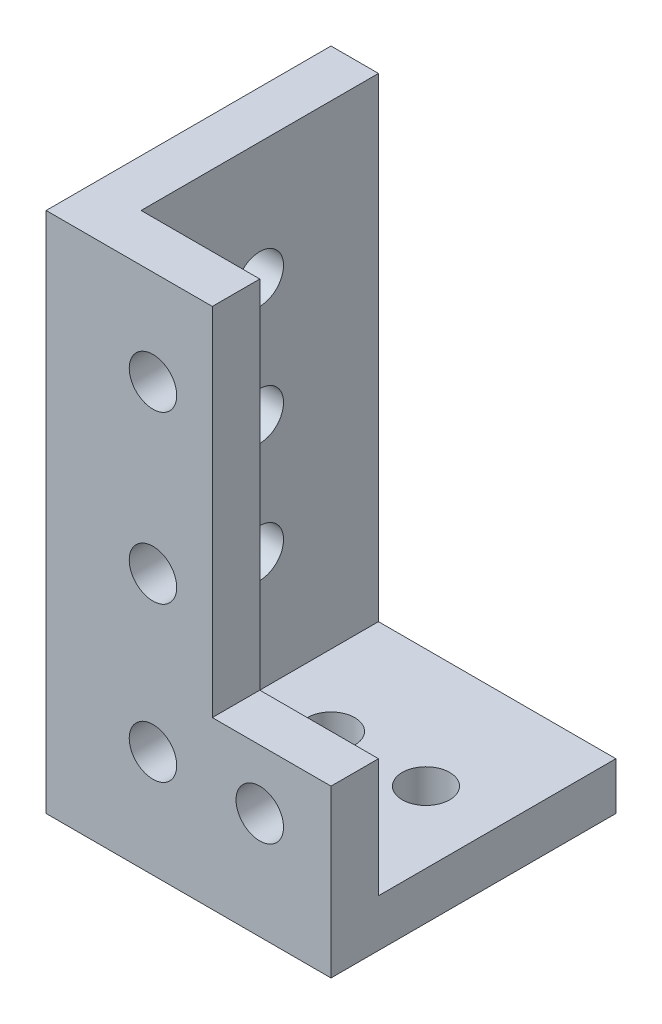
SolidWorks part; units mm, degrees
ref_plane "Front Plane" through (0, 0, 0) normal (0, 0, 1) x (1, 0, 0)
ref_plane "Top Plane" through (0, 0, 0) normal (0, 1, 0) x (1, 0, 0)
ref_plane "Right Plane" through (0, 0, 0) normal (1, 0, 0) x (0, 0, -1)
sketch "Sketch1" plane through (0, 0, 0) normal (0, 0, 1) x (1, 0, 0)
  line L0 (0, 110) -> (10, 110)
  line L1 (0, 0) -> (60, 0)
  line L2 (0, 0) -> (0, 110)
  line L3 (60, 10) -> (60, 0)
  line L5 (10, 110) -> (10, 10)
  line L6 (10, 10) -> (60, 10)
  dimension "D1" = 110
extrude "Boss-Extrude1" add sketch "Sketch1" along normal blind 50
sketch "Sketch2" plane through (0, 0, 50) normal (0, 0, 1) x (1, 0, 0)
  line L0 (0, 110) -> (35, 110)
  line L1 (0, 110) -> (0, 0) construction
  line L2 (10, 110) -> (0, 110) construction
  line L3 (35, 110) -> (35, 35)
  line L4 (35, 35) -> (60, 35)
  line L5 (60, 35) -> (60, 0)
  line L6 (60, 0) -> (60, 10) construction
  line L7 (60, 0) -> (0, 0)
  line L8 (0, 0) -> (0, 110)
  dimension "D1" = 35
  dimension "D2" = 35
extrude "Boss-Extrude2" add sketch "Sketch2" along normal blind 10
sketch "Sketch4" plane through (10, 0, 0) normal (1, 0, 0) x (0, 0, -1)
  line L0 (-25, 110) -> (-25, 10) construction
  line L1 (-50, 110) -> (0, 110) construction
  line L2 (-50, 10) -> (0, 10) construction
  circle A0 centre (-25, 60) radius 5
  circle A1 centre (-25, 85) radius 5
  circle A2 centre (-25, 35) radius 5
  dimension "D1" = 10
  dimension "D2" = 10
  dimension "D3" = 10
  dimension "D4" = 25
  dimension "D5" = 75
extrude "Cut-Extrude1" cut sketch "Sketch4" against normal blind 10
sketch "Sketch5" plane through (0, 10, 0) normal (0, 1, 0) x (1, 0, 0)
  line L0 (60, -25) -> (10, -25) construction
  line L1 (60, -50) -> (60, 0) construction
  line L2 (10, -50) -> (10, 0) construction
  line L3 (35, -25) -> (35, 0) construction
  line L4 (60, 0) -> (10, 0) construction
  circle A0 centre (45, -25) radius 5
  circle A1 centre (25, -25) radius 5
  dimension "D1" = 10
  dimension "D2" = 10
  dimension "D3" = 15
  dimension "D4" = 35
extrude "Cut-Extrude2" cut sketch "Sketch5" against normal blind 10
sketch "Sketch6" plane through (0, 0, 50) normal (0, 0, -1) x (-1, 0, 0)
  line L0 (-60, 22.5) -> (-10, 22.5) construction
  line L1 (-60, 10) -> (-60, 35) construction
  line L2 (-10, 10) -> (-10, 110) construction
  line L3 (-22.5, 110) -> (-22.5, 10) construction
  line L4 (-35, 110) -> (-10, 110) construction
  line L5 (-60, 10) -> (-10, 10) construction
  circle A0 centre (-22.5, 22.5) radius 5
  circle A1 centre (-22.5, 55) radius 5
  circle A2 centre (-22.5, 90) radius 5
  circle A3 centre (-45, 22.5) radius 5
  dimension "D1" = 10
  dimension "D2" = 10
  dimension "D3" = 10
  dimension "D4" = 10
  dimension "D5" = 20
  dimension "D6" = 15
  dimension "D7" = 55
extrude "Cut-Extrude3" cut sketch "Sketch6" against normal blind 10
